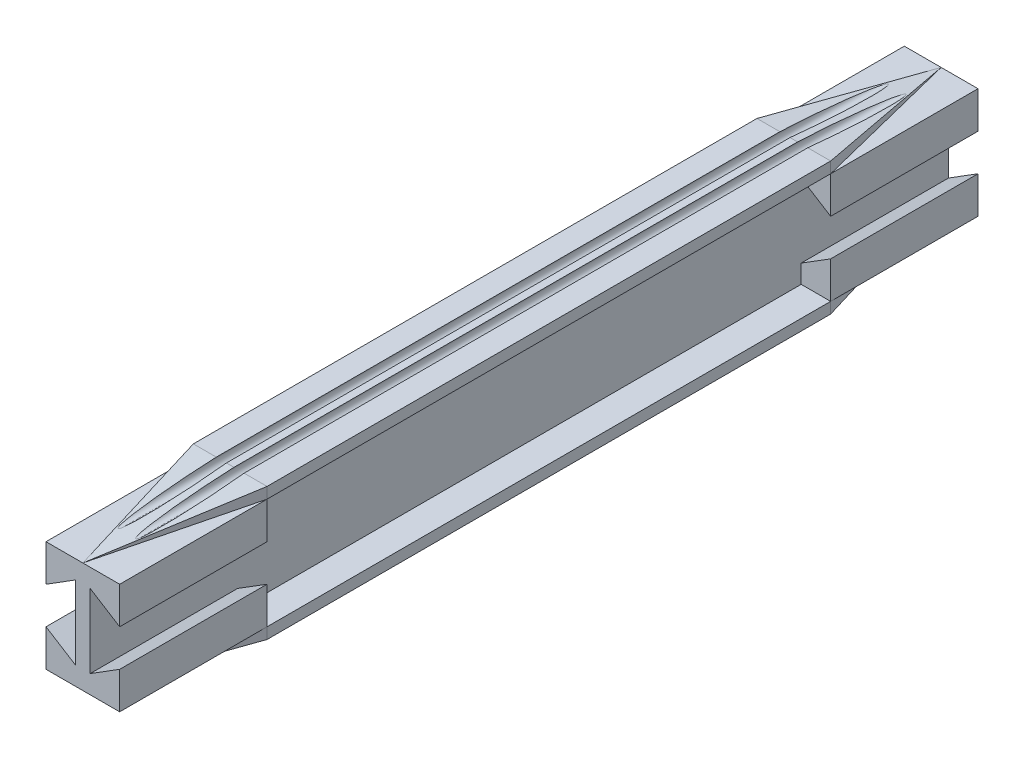
SolidWorks part; units mm, degrees
ref_plane "Front Plane" through (0, 0, 0) normal (0, 0, 1) x (1, 0, 0)
ref_plane "Top Plane" through (0, 0, 0) normal (0, 1, 0) x (1, 0, 0)
ref_plane "Right Plane" through (0, 0, 0) normal (1, 0, 0) x (0, 0, -1)
sketch "Sketch1" plane through (0, 0, 0) normal (1, 0, 0) x (0, 0, -1)
  line L1 (-58.25, -7.5) -> (58.25, -7.5)
  line L2 (-58.25, -7.5) -> (-58.25, 7.5)
  line L3 (-58.25, 7.5) -> (58.25, 7.5)
  line L4 (58.25, -7.5) -> (58.25, 7.5)
  line L5 (-58.25, -7.5) -> (58.25, 7.5) construction
  line L6 (-58.25, 7.5) -> (58.25, -7.5) construction
  point P1 (0, 0)
  dimension "D1" = 116.5
  dimension "D2" = 15
extrude "Boss-Extrude1" add sketch "Sketch1" along normal mid plane 2
sketch "Sketch2" plane through (1, 0, 0) normal (1, 0, 0) x (0, 0, -1)
  line L0 (-58.25, -7.5) -> (58.25, -7.5) construction
  line L1 (58.25, 7.5) -> (38.25, 7.5)
  line L2 (58.25, 7.5) -> (58.25, -7.5)
  line L3 (58.25, -7.5) -> (38.25, -7.5)
  line L4 (38.25, 7.5) -> (38.25, -7.5)
  dimension "D1" = 20
extrude "Boss-Extrude2" add sketch "Sketch2" along normal blind 4
sketch "Sketch3" plane through (0, 0, -38.25) normal (0, 0, 1) x (1, 0, 0)
  line L0 (5, 0) -> (1, 0) construction
  line L1 (5, 7.5) -> (5, -7.5) construction
  line L2 (1, 7.5) -> (1, -7.5) construction
  line L3 (5, 2.5) -> (1, 5)
  line L4 (1, 5) -> (1, -5)
  line L5 (1, -5) -> (5, -2.5)
  line L6 (5, -2.5) -> (5, 2.5)
  point P8 (0, 0)
  point P11 (1.801, 4.7076)
  point P12 (1.6579, -5.0749)
  dimension "D1" = 5
  dimension "D2" = 10
  dimension "D3" = 4
extrude "Cut-Extrude1" cut sketch "Sketch3" against normal through all
mirror "Mirror1" about plane through (0, 0, 0) normal (1, 0, 0) of "Cut-Extrude1", "Boss-Extrude2"
mirror "Mirror2" about plane through (0, 0, 0) normal (0, 0, 1) of "Mirror1", "Boss-Extrude2", "Cut-Extrude1"
sketch "Sketch7" plane through (0, 7.5, 0) normal (0, 1, 0) x (1, 0, 0)
  line L0 (0, -58.25) -> (0, 49941.75) construction
  line L1 (5, -58.25) -> (-5, -58.25) construction
  line L2 (0, -58.25) -> (-5, -38.25)
  line L3 (-5, -38.25) -> (-1, -38.25) construction
  line L4 (-5, -38.25) -> (-5, 38.25)
  line L5 (-5, 38.25) -> (-1, 38.25) construction
  line L6 (-5, 38.25) -> (0, 58.25)
  line L7 (5, 58.25) -> (-5, 58.25) construction
  line L8 (5, 38.25) -> (0, 58.25)
  line L9 (5, -38.25) -> (5, 38.25)
  line L10 (0, -58.25) -> (5, -38.25)
  line L11 (1, 38.25) -> (1, -38.25) construction
  point P4 (0, -58.25)
  dimension "D1" = 4
extrude "Boss-Extrude5" add sketch "Sketch7" along normal blind 1.5
sketch "Sketch8" plane through (-5, 0, 0) normal (-1, 0, 0) x (0, 0, 1)
  line L0 (-38.25, 9) -> (-58.25, 7.5)
  line L1 (-58.25, 7.5) -> (-58.25, 9)
  line L2 (-58.25, 9) -> (-38.25, 9)
  line L3 (0, 9) -> (0, -49991) construction
  line L4 (-38.25, 9) -> (38.25, 9) construction
  line L5 (58.25, 9) -> (38.25, 9)
  line L6 (58.25, 7.5) -> (58.25, 9)
  line L7 (38.25, 9) -> (58.25, 7.5)
  point P17 (0, 9)
extrude "Cut-Extrude2" cut sketch "Sketch8" against normal through all
sketch "Sketch9" plane through (0, 0, 58.25) normal (0, 0, 1) x (1, 0, 0)
  line L0 (0, 7.5) -> (0, -49992.5) construction
  line L1 (5, 7.5) -> (0, 7.5) construction
  circle A0 centre (1.2, 8.7) radius 0.75
  circle A1 centre (-1.2, 8.7) radius 0.75
  point P9 (2.1837, 7.999)
  dimension "D2" = 1.5
  dimension "D1" = 1.2
  dimension "D3" = 1.2
extrude "Cut-Extrude3" cut sketch "Sketch9" against normal through all
mirror "Mirror4" about plane through (0, 0, 0) normal (0, 1, 0) of "Boss-Extrude5", "Cut-Extrude2", "Cut-Extrude3"
